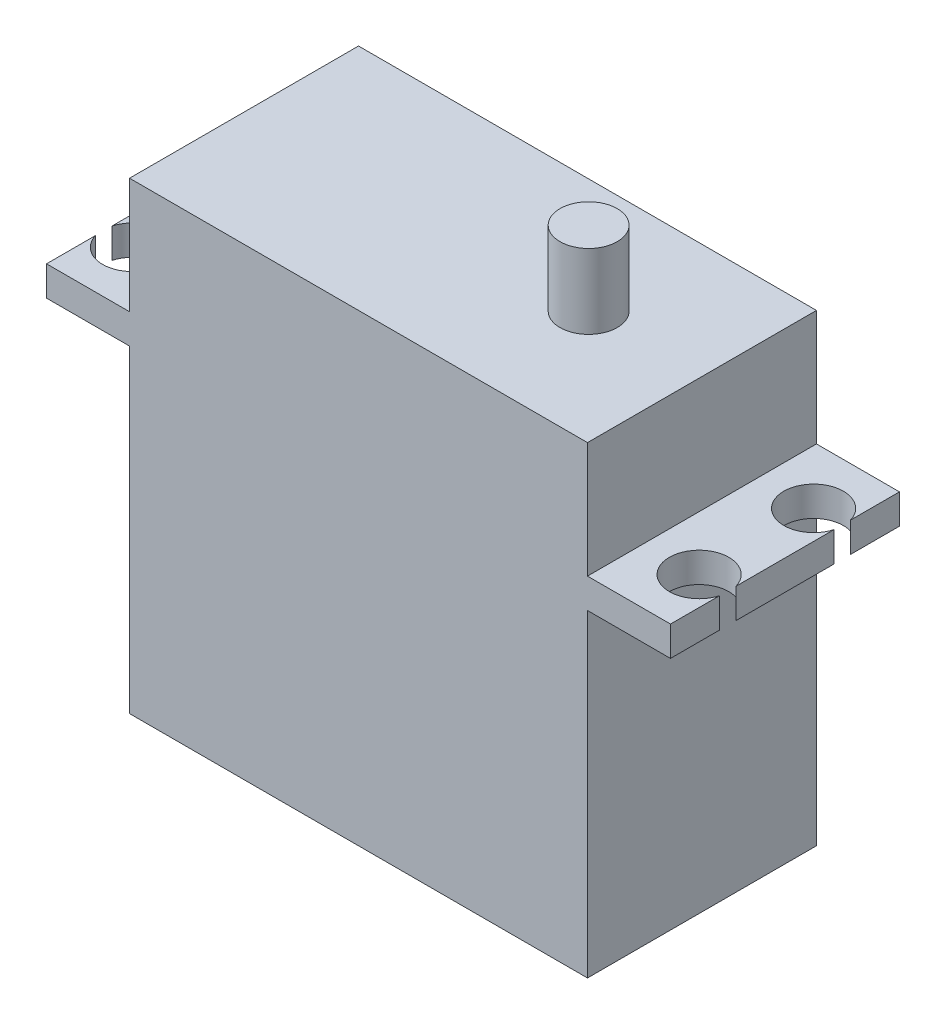
SolidWorks part; units mm, degrees
ref_plane "Front Plane" through (0, 0, 0) normal (0, 0, 1) x (1, 0, 0)
ref_plane "Top Plane" through (0, 0, 0) normal (0, 1, 0) x (1, 0, 0)
ref_plane "Right Plane" through (0, 0, 0) normal (1, 0, 0) x (0, 0, -1)
sketch "Sketch1" plane through (0, 0, 0) normal (0, 1, 0) x (1, 0, 0)
  line L1 (0, 0) -> (40, 0)
  line L2 (0, 0) -> (0, -20)
  line L3 (0, -20) -> (40, -20)
  line L4 (40, 0) -> (40, -20)
  dimension "D1" = 40
  dimension "D2" = 20
extrude "Boss-Extrude1" add sketch "Sketch1" along normal blind 40.5
sketch "Sketch2" plane through (0, 40.5, 0) normal (0, 1, 0) x (1, 0, 0)
  line L0 (40, -10) -> (30.1, -10)
  line L1 (40, -20) -> (40, 0) construction
  circle A0 centre (30.1, -10) radius 2.5
  dimension "D1" = 9.9
extrude "Boss-Extrude2" add sketch "Sketch2" along normal blind 6.5
sketch "Sketch3" plane through (0, 0, 0) normal (-1, 0, 0) x (0, 0, 1)
  line L0 (20, 0) -> (20, 27.8)
  line L1 (20, 40.5) -> (20, 0) construction
  line L2 (20, 27.8) -> (0, 27.8)
  line L3 (0, 40.5) -> (0, 0) construction
  line L4 (0, 27.8) -> (0, 30.4)
  line L5 (0, 30.4) -> (20, 30.4)
  line L6 (20, 30.4) -> (20, 27.8)
  line M4 (20, 0) -> (20, 40.5)
  line M6 (0, 40.5) -> (0, 0)
  dimension "D1" = 27.8
  dimension "D2" = 2.6
extrude "Boss-Extrude3" add sketch "Sketch3" along normal blind 7.25 contours L5 L2 M6 M4
sketch "Sketch4" plane through (40, 0, 0) normal (1, 0, 0) x (0, 0, -1)
  line L0 (-20, 0) -> (-20, 27.8)
  line L1 (-20, 27.8) -> (0, 27.8)
  line L2 (0, 27.8) -> (0, 30.4)
  line L3 (0, 30.4) -> (-20, 30.4)
  line L4 (-20, 30.4) -> (-20, 27.8)
  line M2 (0, 0) -> (0, 40.5)
  line M4 (-20, 40.5) -> (-20, 0)
extrude "Boss-Extrude4" add sketch "Sketch4" along normal blind 7.25 contours L3 L1 M2 M4
sketch "Sketch5" plane through (0, 30.4, 0) normal (0, 1, 0) x (1, 0, 0)
  line L0 (47.25, 0) -> (44.75, 0)
  line L1 (47.25, 0) -> (40, 0) construction
  line L2 (44.75, 0) -> (44.75, -5)
  line L3 (44.75, -5) -> (44.75, -15)
  line L4 (-7.25, 0) -> (-4.75, 0)
  line L5 (-7.25, 0) -> (0, 0) construction
  line L6 (-4.75, 0) -> (-4.75, -5)
  line L7 (-4.75, -5) -> (-4.75, -15)
  circle A0 centre (44.75, -5) radius 2.6
  circle A1 centre (44.75, -15) radius 2.6
  circle A2 centre (-4.75, -15) radius 2.6
  circle A3 centre (-4.75, -5) radius 2.6
  dimension "D1" = 2.5
  dimension "D2" = 5
  dimension "D3" = 10
  dimension "D4" = 2.5
extrude "Cut-Extrude5" cut sketch "Sketch5" against normal blind 7.25 contours A1 | A0 | A2 | A3
